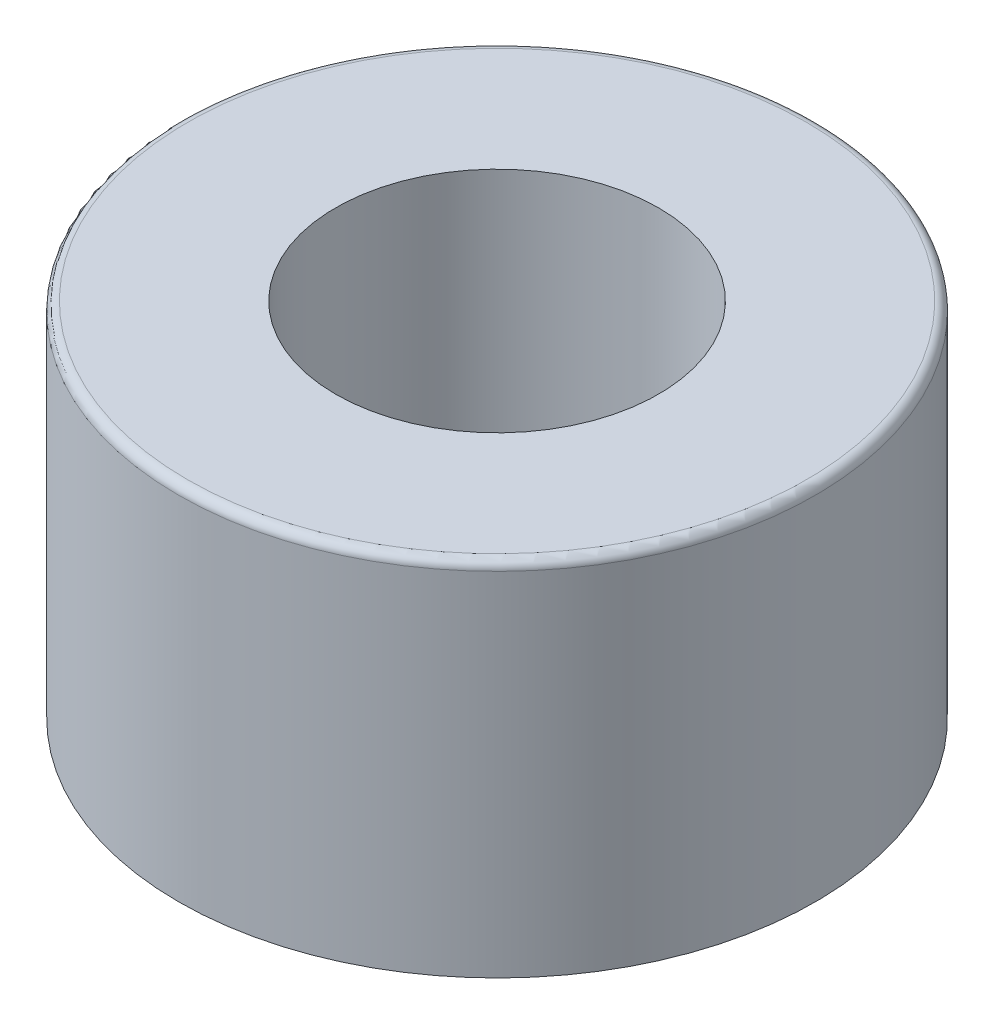
SolidWorks part; units mm, degrees
ref_plane "Front Plane" through (0, 0, 0) normal (0, 0, 1) x (1, 0, 0)
ref_plane "Top Plane" through (0, 0, 0) normal (0, 1, 0) x (1, 0, 0)
ref_plane "Right Plane" through (0, 0, 0) normal (1, 0, 0) x (0, 0, -1)
sketch "Sketch1" plane through (0, 0, 0) normal (0, 1, 0) x (1, 0, 0)
  circle A0 centre (0, 0) radius 9.017
  circle A1 centre (0, 0) radius 4.572
extrude "Boss-Extrude1" add sketch "Sketch1" along normal blind 10.2235
fillet "Fillet2" radius 0.254 1 edges at (0, 10.2235, 9.017)
